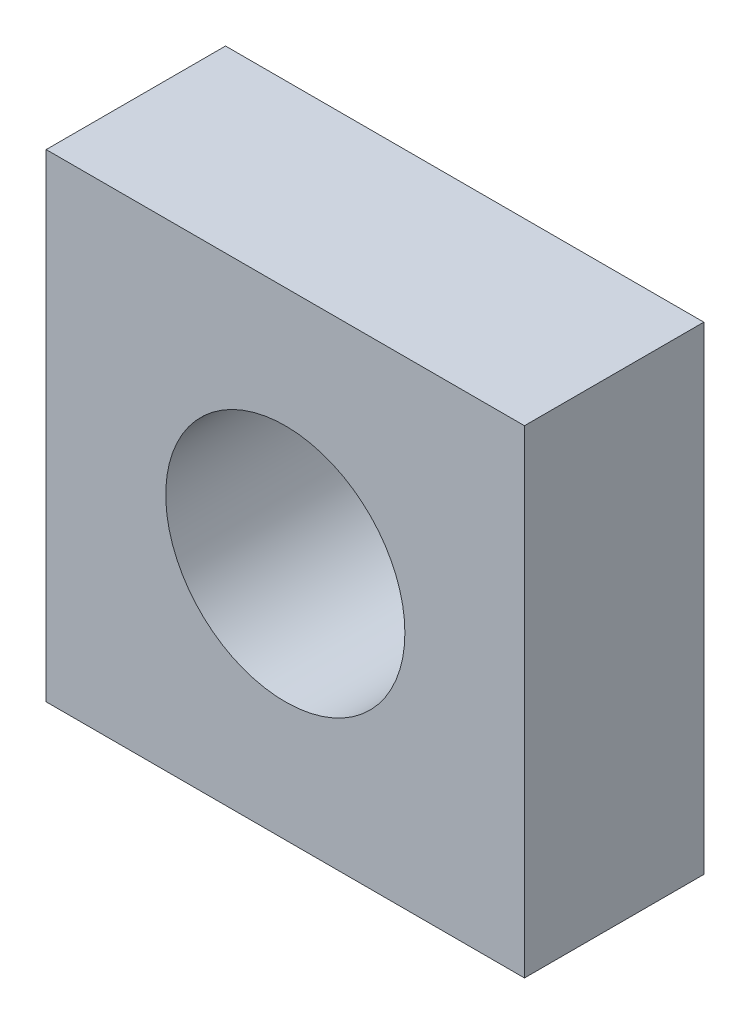
SolidWorks part; units mm, degrees
material "A286 Súper aleación a base de hierro"
ref_plane "Alzado" through (0, 0, 0) normal (0, 0, 1) x (1, 0, 0)
ref_plane "Planta" through (0, 0, 0) normal (0, 1, 0) x (1, 0, 0)
ref_plane "Vista lateral" through (0, 0, 0) normal (1, 0, 0) x (0, 0, -1)
sketch "Croquis1" plane through (0, 0, 0) normal (0, 0, 1) x (1, 0, 0)
  line L0 (570, 580) -> (570, 500)
  line L1 (570, 580) -> (650, 580)
  line L2 (650, 580) -> (650, 500)
  line L3 (650, 500) -> (570, 500)
  circle A0 centre (610, 540) radius 20
  point P8 (582.3454, 500)
  dimension "D6" = 40
  dimension "D5" = 40
  dimension "D1" = 80
  dimension "D2" = 80
  dimension "D3" = 40
  dimension "D4" = 80
extrude "Saliente-Extruir2" add sketch "Croquis1" along normal blind 30
